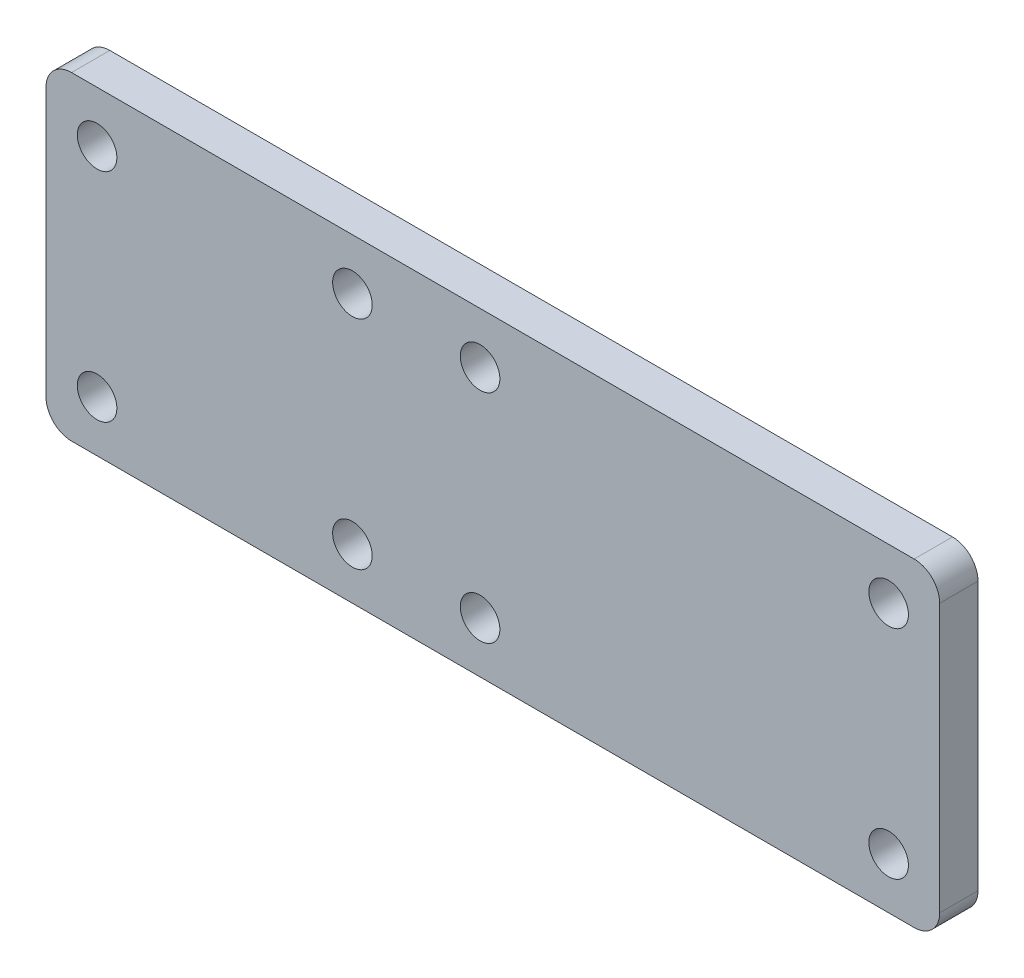
SolidWorks part; units mm, degrees
material "Thornel Mat VMA"
ref_plane "前视基准面" through (0, 0, 0) normal (0, 0, 1) x (1, 0, 0)
ref_plane "上视基准面" through (0, 0, 0) normal (0, 1, 0) x (1, 0, 0)
ref_plane "右视基准面" through (0, 0, 0) normal (1, 0, 0) x (0, 0, -1)
sketch "草图1" plane through (0, 0, 0) normal (0, 0, 1) x (1, 0, 0)
  line L1 (-35, -12.5) -> (35, -12.5)
  line L2 (-35, -12.5) -> (-35, 12.5)
  line L3 (-35, 12.5) -> (35, 12.5)
  line L4 (35, -12.5) -> (35, 12.5)
  line L5 (0, 12.5) -> (0, -12.5) construction
  line L6 (-35, 0) -> (35, 0) construction
  point P0 (0, 0)
  dimension "D1" = 25
  dimension "D2" = 70
extrude "凸台-拉伸1" add sketch "草图1" along normal blind 3
sketch "草图2" plane through (0, 0, 3) normal (0, 0, 1) x (1, 0, 0)
  line L0 (35, -12.5) -> (35, 12.5) construction
  line L1 (-1, -8.5) -> (31, -8.5) construction
  line L2 (-1, -8.5) -> (-1, 8.5) construction
  line L3 (-1, 8.5) -> (31, 8.5) construction
  line L4 (31, -8.5) -> (31, 8.5) construction
  line L5 (15, 8.5) -> (15, -8.5) construction
  line L6 (-1, 0) -> (31, 0) construction
  line L8 (-35, 12.5) -> (-35, -12.5) construction
  line L9 (-31, -8.5) -> (-11, -8.5) construction
  line L10 (-31, -8.5) -> (-31, 8.5) construction
  line L11 (-31, 8.5) -> (-11, 8.5) construction
  line L12 (-11, -8.5) -> (-11, 8.5) construction
  line L13 (-21, 8.5) -> (-21, -8.5) construction
  line L14 (-31, 0) -> (-11, 0) construction
  circle A0 centre (31, 8.5) radius 1.55
  circle A1 centre (-1, 8.5) radius 1.55
  circle A2 centre (-1, -8.5) radius 1.55
  circle A3 centre (31, -8.5) radius 1.55
  circle A4 centre (-11, -8.5) radius 1.55
  circle A5 centre (-31, -8.5) radius 1.55
  circle A6 centre (-31, 8.5) radius 1.55
  circle A7 centre (-11, 8.5) radius 1.55
  point P0 (15, 0)
  point P10 (-21, 0)
  dimension "D4" = 3.1
  dimension "D1" = 4
  dimension "D2" = 32
  dimension "D3" = 17
  dimension "D5" = 4
  dimension "D6" = 20
extrude "切除-拉伸1" cut sketch "草图2" against normal blind 3
fillet "圆角1" radius 2 4 edges at (35, -12.5, 1.5) (-35, -12.5, 1.5) (-35, 12.5, 1.5) (35, 12.5, 1.5)
